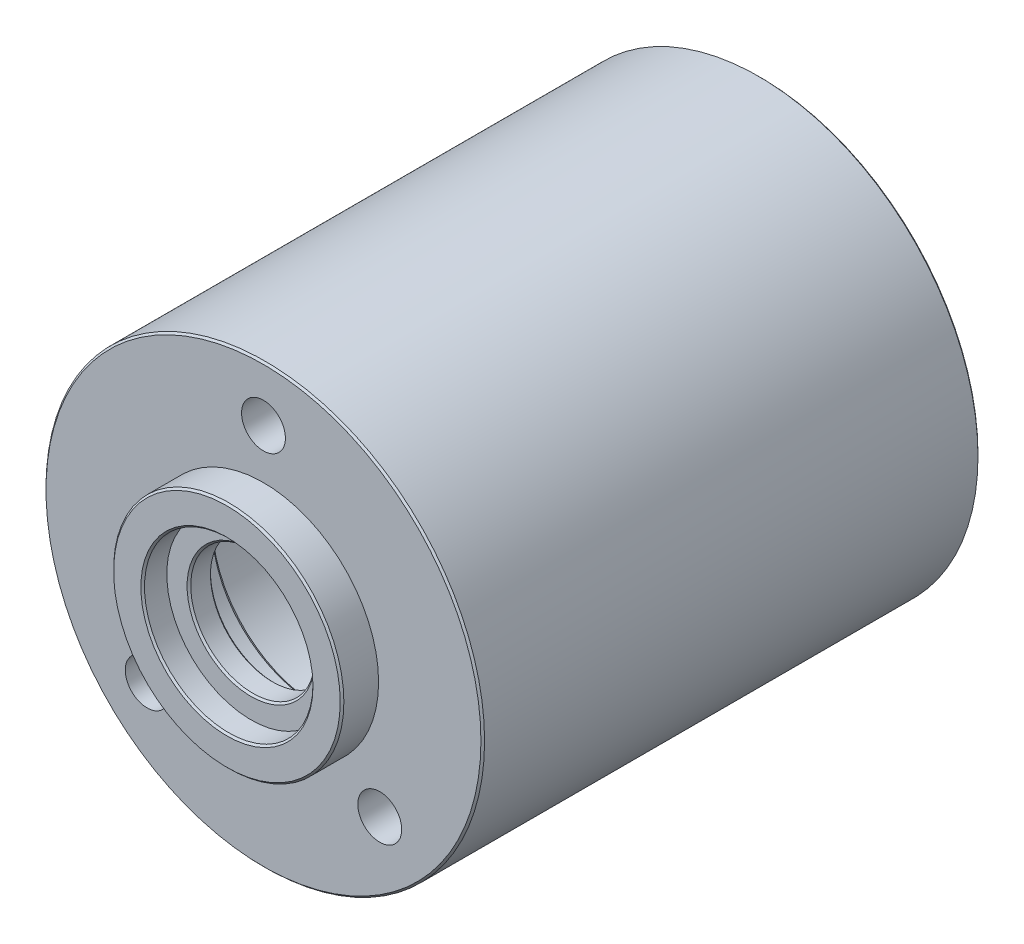
SolidWorks part; units mm, degrees
material "2P Cast Iron"
ref_plane "Front Plane" through (0, 0, 0) normal (0, 0, 1) x (1, 0, 0)
ref_plane "Top Plane" through (0, 0, 0) normal (0, 1, 0) x (1, 0, 0)
ref_plane "Right Plane" through (0, 0, 0) normal (1, 0, 0) x (0, 0, -1)
sketch "Sketch1" plane through (0, 0, 0) normal (1, 0, 0) x (0, 0, -1)
  line L0 (0, 0) -> (155.119, 0) construction
  line L1 (0, 0) -> (0, 95.1189) construction
  line L2 (0.25, 15.75) -> (5, 15.75)
  line L3 (3.3, 11.525) -> (3.3, 8.75)
  line L4 (0, 11.775) -> (0, 15.5)
  line L5 (3.55, 8.5) -> (6.25, 8.5)
  line L6 (6.5, 8.75) -> (6.5, 14.025)
  line L7 (5, 15.75) -> (5, 29.75)
  line L8 (6.5, 14.025) -> (12, 14.025)
  line L9 (5.25, 30) -> (72.75, 30)
  line L11 (0.25, 11.525) -> (3.3, 11.525)
  line L12 (12.575, 14.6) -> (72.75, 14.6)
  line L13 (73, 14.85) -> (73, 26.85)
  line L14 (73, 26.85) -> (72, 26.85)
  line L15 (72, 26.85) -> (72, 28.85)
  line L16 (72, 28.85) -> (73, 28.85)
  line L17 (73, 28.85) -> (73, 29.75)
  line L18 (3.3, 8.75) -> (3.55, 8.5)
  line L19 (6.25, 8.5) -> (6.5, 8.75)
  line L20 (12, 14.025) -> (12.575, 14.6)
  line L21 (0.25, 11.525) -> (0, 11.775)
  line L22 (0, 15.5) -> (0.25, 15.75)
  line L23 (5, 29.75) -> (5.25, 30)
  line L24 (72.75, 30) -> (73, 29.75)
  line L25 (72.75, 14.6) -> (73, 14.85)
  point P5 (6.5, 8.5)
  point P6 (0, 15.75)
  point P8 (0, 11.525)
  point P9 (12.25, 14.025)
  point P12 (73, 14.6)
  point P13 (5, 30)
  point P14 (72.5, 26.85)
  point P15 (73, 30)
  point P29 (3.3, 8.5)
  dimension "D6" = 68
  dimension "D1" = 23.05
  dimension "D2" = 31.5
  dimension "D3" = 0
  dimension "D4" = 5
  dimension "D5" = 60
  dimension "D7" = 57.7
  dimension "D8" = 2
  dimension "D9" = 1
  dimension "D10" = 29.2
  dimension "D11" = 45
  dimension "D12" = 3.3
  dimension "D13" = 5.5
  dimension "D14" = 17
  dimension "D24" = 3.2
  dimension "D15" = 28.05
revolve "Revolve1" add sketch "Sketch1" angle 360 about L0
sketch "Sketch2" plane through (0, 0, -5) normal (0, 0, 1) x (1, 0, 0)
  circle A0 centre (15.9099, -15.9099) radius 3
  circle A1 centre (-15.9099, -15.9099) radius 3
  circle A2 centre (0, 22.5) radius 3
  point P6 (0, 0)
extrude "Cut-Extrude1" cut sketch "Sketch2" against normal blind 23 contours A2 | A1 | A0
cosmetic thread "Cosmetic Thread1" parameters "D2"=8
cosmetic thread "Cosmetic Thread2" parameters "D2"=8
cosmetic thread "Cosmetic Thread3" parameters "D2"=8
sketch "Sketch3" plane through (0, 0, -73) normal (0, 0, -1) x (-1, 0, 0)
  line L0 (0, 0) -> (0, -19.7637) construction
  circle A1 centre (-12.45, -17.15) radius 4.25 construction
  circle A10 centre (0, 21.2) radius 4.25 construction
  arc A16 (14.8931, 3.343) -> (20.7474, 4.657) centre (17.8203, 4) ccw construction
  arc A17 (14.8931, 3.343) -> (13.8082, 6.505) centre (0, 0) ccw construction
  arc A18 (19.236, 9.062) -> (13.8082, 6.505) centre (16.5221, 7.7835) ccw construction
  arc A19 (20.7474, 4.657) -> (19.236, 9.062) centre (0, 0) ccw construction
  circle A22 centre (12.45, -17.15) radius 4.25 construction
  arc A27 (-13.8082, 6.505) -> (-19.236, 9.062) centre (-16.5221, 7.7835) ccw construction
  arc A28 (-13.8082, 6.505) -> (-14.8931, 3.343) centre (0, 0) ccw construction
  arc A29 (-20.7474, 4.657) -> (-14.8931, 3.343) centre (-17.8203, 4) ccw construction
  arc A30 (-19.236, 9.062) -> (-20.7474, 4.657) centre (0, 0) ccw construction
  circle A35 centre (0, 0) radius 19.7637 construction
  circle A36 centre (0, -19.7637) radius 3.25
  circle A37 centre (-18.7964, -6.1073) radius 3.25
  circle A38 centre (-11.6168, 15.9892) radius 3.25
  circle A39 centre (11.6168, 15.9892) radius 3.25
  circle A40 centre (18.7964, -6.1073) radius 3.25
  circle A41 centre (0, 21.2) radius 3.4
  circle A42 centre (-12.45, -17.15) radius 3.4
  circle A43 centre (12.45, -17.15) radius 3.4
  circle A44 centre (0, 0) radius 21.2637 construction
  circle A45 centre (-20.1127, 6.901) radius 3.6974
  circle A46 centre (20.1127, 6.901) radius 3.6974
  dimension "D1" = 39.5274
  dimension "D2" = 6.5
  dimension "D5" = 6.8
  dimension "D3" = 19.7637
  dimension "D4" = 5
extrude "Cut-Extrude2" cut sketch "Sketch3" against normal blind 23 contours A41 | A39 | A46 | A40 | A43 | A36 | A42 | A37 | A45 | A38
cosmetic thread "Cosmetic Thread4" parameters "D2"=8
cosmetic thread "Cosmetic Thread5" parameters "D2"=8
cosmetic thread "Cosmetic Thread6" parameters "D2"=8
